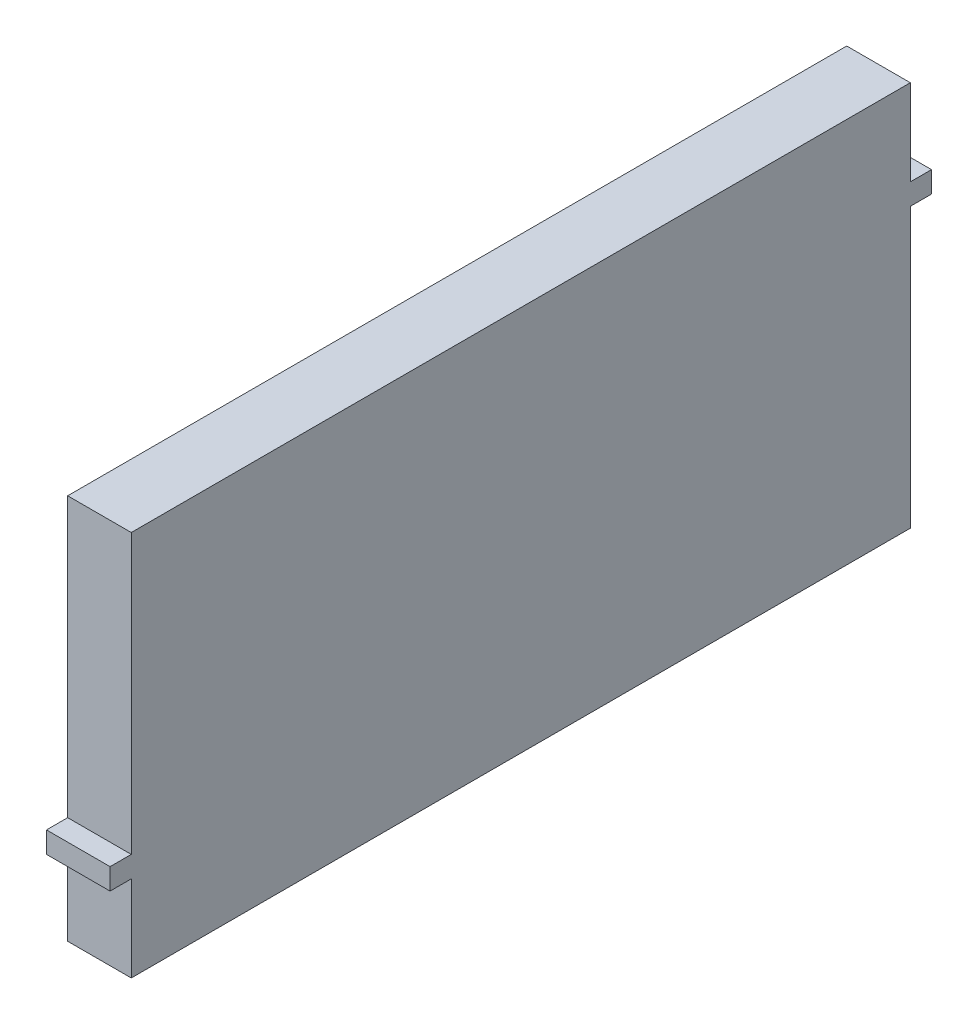
SolidWorks part; units mm, degrees
material "Balsa"
ref_plane "Front Plane" through (0, 0, 0) normal (0, 0, 1) x (1, 0, 0)
ref_plane "Top Plane" through (0, 0, 0) normal (0, 1, 0) x (1, 0, 0)
ref_plane "Right Plane" through (0, 0, 0) normal (1, 0, 0) x (0, 0, -1)
sketch "Sketch1" plane through (243.0177, 0, 0) normal (1, 0, 0) x (0, 0, -1)
  line L0 (-442.7124, 419.518) -> (-439.5374, 419.518) construction
  line L1 (-442.7124, 419.518) -> (-439.5374, 419.518) construction
  line L2 (-442.7124, 361.733) -> (-439.5374, 361.733) construction
  line L3 (-442.7124, 361.733) -> (-439.5374, 361.733) construction
  line L4 (-439.5374, 406.6592) -> (-442.7124, 406.6592)
  line L5 (-442.7124, 406.6592) -> (-442.7124, 403.4842)
  line L6 (-442.7124, 403.4842) -> (-439.5374, 403.4842)
  line L7 (-439.5374, 403.4842) -> (-439.5374, 406.6592)
  line L8 (-439.5374, 406.6592) -> (-442.7124, 406.6592)
  line L10 (-442.7124, 403.4842) -> (-439.5374, 403.4842)
  line L11 (-439.5374, 403.4842) -> (-439.5374, 406.6592)
  line L12 (-562.5687, 419.518) -> (-559.3937, 419.518) construction
  line L13 (-562.5687, 419.518) -> (-559.3937, 419.518) construction
  line L14 (-559.3937, 419.518) -> (-442.7124, 419.518)
  line L15 (-562.5687, 361.733) -> (-559.3937, 361.733) construction
  line L16 (-559.3937, 377.7667) -> (-562.5687, 377.7667)
  line L17 (-562.5687, 377.7667) -> (-562.5687, 374.5917)
  line L18 (-562.5687, 374.5917) -> (-559.3937, 374.5917)
  line L19 (-559.3937, 374.5917) -> (-559.3937, 377.7667)
  line L20 (-559.3937, 377.7667) -> (-562.5687, 377.7667)
  line L21 (-562.5687, 377.7667) -> (-562.5687, 374.5917)
  line L22 (-562.5687, 374.5917) -> (-559.3937, 374.5917)
  line L25 (-442.7124, 406.6592) -> (-442.7124, 419.518)
  line L26 (-442.7124, 403.4842) -> (-442.7124, 361.733)
  line L28 (-559.3937, 361.733) -> (-559.3937, 374.5917)
  line L29 (-559.3937, 377.7667) -> (-559.3937, 419.518)
  line L30 (-562.5687, 361.733) -> (-559.3937, 361.733) construction
  line L31 (-442.7124, 361.733) -> (-559.3937, 361.733)
  dimension "D1" = 0
  dimension "D2" = 0
extrude "Boss-Extrude1" add sketch "Sketch1" along normal up to surface (9.525 mm away)
